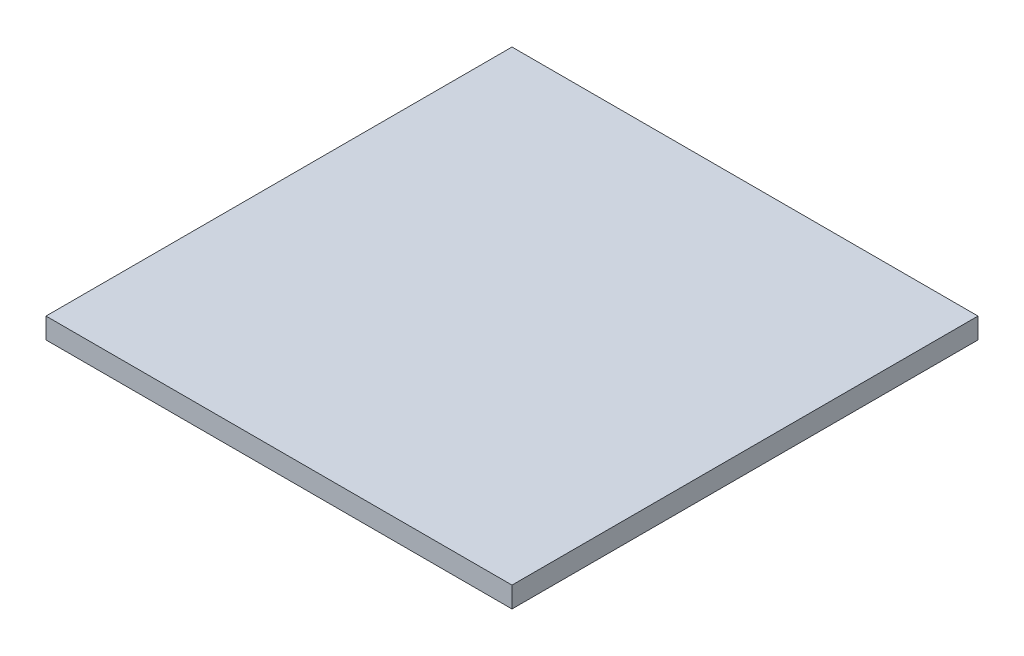
SolidWorks part; units mm, degrees
ref_plane "Front Plane" through (0, 0, 0) normal (0, 0, 1) x (1, 0, 0)
ref_plane "Top Plane" through (0, 0, 0) normal (0, 1, 0) x (1, 0, 0)
ref_plane "Right Plane" through (0, 0, 0) normal (1, 0, 0) x (0, 0, -1)
sketch "Sketch1" plane through (0, 0, 0) normal (0, 1, 0) x (1, 0, 0)
  line L1 (0, 0) -> (-571.5, 0)
  line L2 (0, 0) -> (0, 571.5)
  line L3 (0, 571.5) -> (-571.5, 571.5)
  line L4 (-571.5, 0) -> (-571.5, 571.5)
  dimension "D1" = 571.5
  dimension "D2" = 571.5
extrude "Boss-Extrude1" add sketch "Sketch1" along normal blind 25.4
